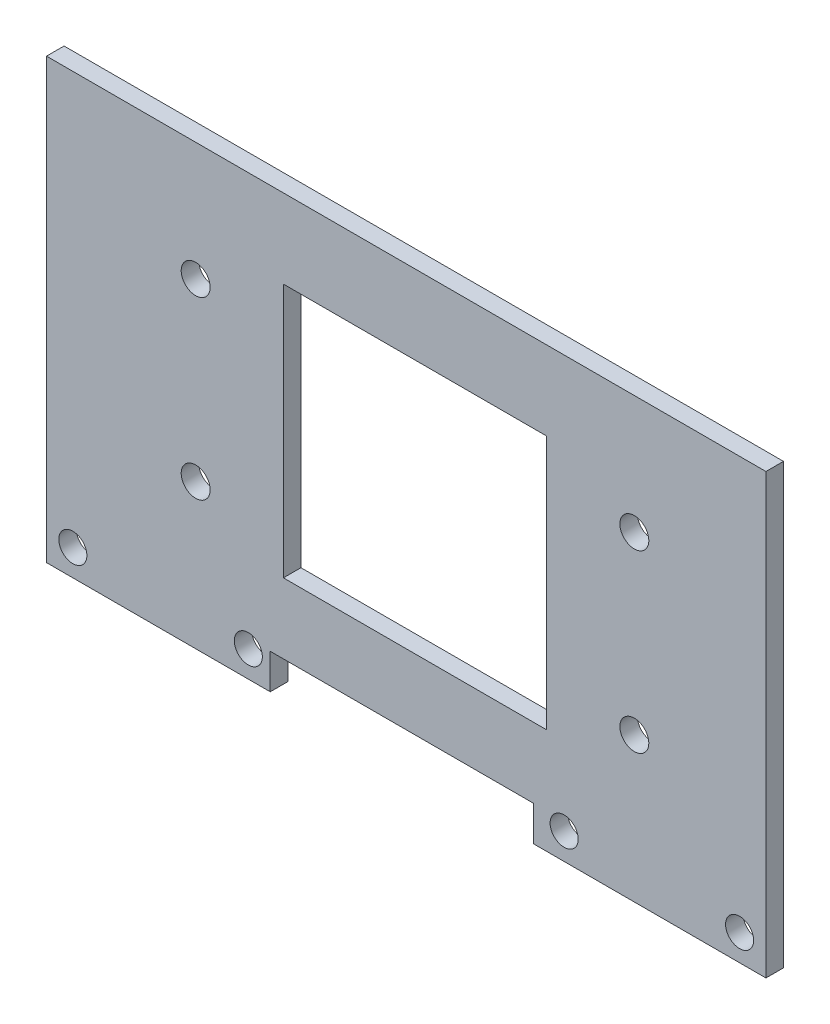
SolidWorks part; units mm, degrees
material "环氧板"
ref_plane "前视基准面" through (0, 0, 0) normal (0, 0, 1) x (1, 0, 0)
ref_plane "上视基准面" through (0, 0, 0) normal (0, 1, 0) x (1, 0, 0)
ref_plane "右视基准面" through (0, 0, 0) normal (1, 0, 0) x (0, 0, -1)
other "Configuration Table"
sketch "草图1" plane through (0, 0, 0) normal (0, 0, 1) x (1, 0, 0)
  line L0 (0, 0) -> (0, 46.767) construction
  line L1 (-40, 25) -> (40, 25)
  line L2 (-40, 25) -> (-40, -25)
  line L3 (-40, -25) -> (40, -25)
  line L4 (40, 25) -> (40, -25)
  line L5 (-40, 25) -> (40, -25) construction
  line L6 (-40, -25) -> (40, 25) construction
  line L7 (-15, 16) -> (15, 16)
  line L8 (-15, 16) -> (-15, -13)
  line L9 (-15, -13) -> (15, -13)
  line L10 (15, 16) -> (15, -13)
  point P0 (0, 0)
  dimension "D3" = 12
  dimension "D1" = 50
  dimension "D2" = 80
  dimension "D4" = 41
  dimension "D5" = 30
extrude "凸台-拉伸1" add sketch "草图1" along normal blind 2
sketch "草图5" plane through (0, 0, 2) normal (0, 0, 1) x (1, 0, 0)
  line L1 (-40, 25) -> (-42, 25)
  line L2 (-40, 25) -> (-40, -25)
  line L3 (-40, -25) -> (-42, -25)
  line L4 (-42, 25) -> (-42, -25)
  dimension "D1" = 2
extrude "凸台-拉伸2" add sketch "草图5" against normal blind 2
sketch "草图2" plane through (0, 0, 2) normal (0, 0, 1) x (1, 0, 0)
  line L0 (-42, -25) -> (40, -25) construction
  line L1 (-15, -25) -> (15, -25)
  line L2 (-15, -25) -> (-15, -21)
  line L3 (-15, -21) -> (15, -21)
  line L4 (15, -25) -> (15, -21)
  line L5 (0, 0) -> (0, -40.2) construction
  dimension "D1" = 30
  dimension "D2" = 4
extrude "切除-拉伸1" cut sketch "草图2" against normal through all
sketch "草图3" plane through (0, 0, 2) normal (0, 0, 1) x (1, 0, 0)
  line L1 (-42, -25) -> (-15, -25) construction
  line L2 (0, 0) -> (0, -38.9243) construction
  line L3 (-42, 25) -> (-42, -25) construction
  circle A0 centre (-39, -22) radius 1.6
  circle A1 centre (-19, -22) radius 1.6
  circle A2 centre (17, -22) radius 1.6
  circle A3 centre (37, -22) radius 1.6
  dimension "D1" = 20
  dimension "D2" = 3.2
  dimension "D5" = 17
  dimension "D6" = 20
  dimension "D3" = 3
  dimension "D4" = 3
extrude "切除-拉伸2" cut sketch "草图3" against normal through all
sketch "草图4" plane through (0, 0, 2) normal (0, 0, 1) x (1, 0, 0)
  line L0 (0, 0) -> (0, 31.4061) construction
  line L1 (20, 20) -> (22.3, 20)
  line L2 (20, 20) -> (20, -5.3)
  line L3 (20, -5.3) -> (22.3, -5.3)
  line L4 (22.3, 20) -> (22.3, -5.3)
  line L5 (-22.3, 20) -> (-22.3, -5.3)
  line L6 (-20, -5.3) -> (-22.3, -5.3)
  line L7 (-20, 20) -> (-20, -5.3)
  line L8 (-20, 20) -> (-22.3, 20)
  line L9 (40, 25) -> (-42, 25) construction
  dimension "D1" = 2.3
  dimension "D2" = 25.3
  dimension "D3" = 20
  dimension "D4" = 5
extrude "切除-拉伸3" [suppressed] cut sketch "草图4" against normal through all
sketch "草图6" plane through (0, 0, 2) normal (0, 0, 1) x (1, 0, 0)
  line L1 (-15, -25) -> (-16.5, -25)
  line L2 (-15, -25) -> (-15, -21)
  line L3 (-15, -21) -> (-16.5, -21)
  line L4 (-16.5, -25) -> (-16.5, -21)
  dimension "D1" = 1.5
extrude "切除-拉伸4" cut sketch "草图6" against normal through all
sketch "草图7" plane through (0, 0, 2) normal (0, 0, 1) x (1, 0, 0)
  line L0 (15, -21) -> (-16.5, -21) construction
  line L1 (15, -25) -> (13.5, -25)
  line L2 (15, -25) -> (15, -21)
  line L3 (15, -21) -> (13.5, -21)
  line L4 (13.5, -25) -> (13.5, -21)
  dimension "D1" = 1.5
extrude "凸台-拉伸3" add sketch "草图7" against normal blind 2
sketch "草图8" plane through (0, 0, 2) normal (0, 0, 1) x (1, 0, 0)
  line L0 (-15, 1.5) -> (-56.7733, 1.5) construction
  line L1 (-15, 16) -> (-15, -13) construction
  line L2 (0, 0) -> (0, 47.1271) construction
  circle A0 centre (-25, 11.5) radius 1.65
  circle A1 centre (25, 11.5) radius 1.65
  circle A2 centre (-25, -8.5) radius 1.65
  circle A3 centre (25, -8.5) radius 1.65
  dimension "D2" = 3.3
  dimension "D3" = 20
  dimension "D1" = 25
extrude "切除-拉伸5" cut sketch "草图8" against normal through all
